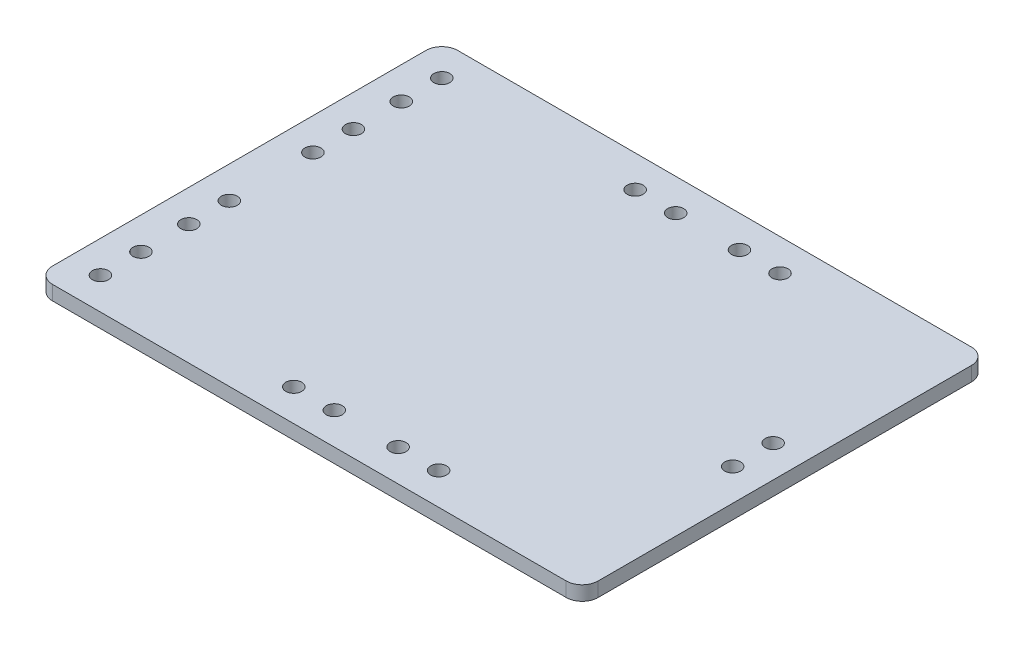
SolidWorks part; units mm, degrees
ref_plane "Plano frontal" through (0, 0, 0) normal (0, 0, 1) x (1, 0, 0)
ref_plane "Plano superior" through (0, 0, 0) normal (0, 1, 0) x (1, 0, 0)
ref_plane "Plano direito" through (0, 0, 0) normal (1, 0, 0) x (0, 0, -1)
sketch "Esboço1" plane through (0, 0, 0) normal (0, 1, 0) x (1, 0, 0)
  line L1 (17.1, -12.7) -> (-17.1, -12.7)
  line L2 (17.1, -12.7) -> (17.1, 12.7)
  line L3 (17.1, 12.7) -> (-17.1, 12.7)
  line L4 (-17.1, -12.7) -> (-17.1, 12.7)
  line L5 (17.1, -12.7) -> (-17.1, 12.7) construction
  line L6 (17.1, 12.7) -> (-17.1, -12.7) construction
  point P0 (0, 0)
  dimension "D1" = 25.4
  dimension "D2" = 34.2
extrude "Ressalto-extrusão1" add sketch "Esboço1" along normal mid plane 0.9
sketch "Esboço2" plane through (0, 0.45, 0) normal (0, 1, 0) x (1, 0, 0)
  line L0 (0, 0) -> (0, 12.7) construction
  line L1 (17.1, 12.7) -> (-17.1, 12.7) construction
  line L2 (0, 0) -> (17.1, 0) construction
  line L3 (17.1, -12.7) -> (17.1, 12.7) construction
  line L4 (-17.1, 12.7) -> (-17.1, -12.7) construction
  circle A0 centre (15.1, 1.27) radius 0.5
  circle A1 centre (15.1, -1.27) radius 0.5
  circle A2 centre (-2.98, 10.7) radius 0.5
  circle A3 centre (-0.44, 10.7) radius 0.5
  circle A4 centre (3.56, 10.7) radius 0.5
  circle A5 centre (6.1, 10.7) radius 0.5
  circle A6 centre (-15.1, 2.62) radius 0.5
  circle A7 centre (-15.1, 5.16) radius 0.5
  circle A8 centre (-15.1, 8.16) radius 0.5
  circle A9 centre (-15.1, 10.7) radius 0.5
  circle A10 centre (6.1, -10.7) radius 0.5
  circle A11 centre (3.56, -10.7) radius 0.5
  circle A12 centre (-0.44, -10.7) radius 0.5
  circle A13 centre (-2.98, -10.7) radius 0.5
  circle A14 centre (-15.1, -10.7) radius 0.5
  circle A15 centre (-15.1, -8.16) radius 0.5
  circle A16 centre (-15.1, -5.16) radius 0.5
  circle A17 centre (-15.1, -2.62) radius 0.5
  dimension "D1" = 1
  dimension "D2" = 1
  dimension "D3" = 1
  dimension "D4" = 2.54
  dimension "D5" = 2
  dimension "D6" = 2.54
  dimension "D7" = 3
  dimension "D8" = 2
  dimension "D9" = 11
  dimension "D10" = 2.54
  dimension "D11" = 4
  dimension "D12" = 2.54
  dimension "D13" = 2
  dimension "D14" = 2
  dimension "D15" = 2.54
extrude "Corte-extrusão1" cut sketch "Esboço2" against normal through all
fillet "Filete1" radius 1 4 edges at (-17.1, 0, -12.7) (17.1, 0, -12.7) (17.1, 0, 12.7) (-17.1, 0, 12.7)
